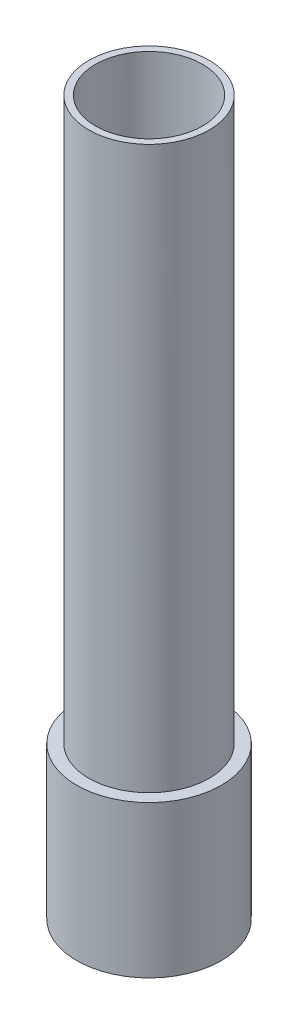
SolidWorks part; units mm, degrees
material "AISI 1020"
ref_plane "Front Plane" through (0, 0, 0) normal (0, 0, 1) x (1, 0, 0)
ref_plane "Top Plane" through (0, 0, 0) normal (0, 1, 0) x (1, 0, 0)
ref_plane "Right Plane" through (0, 0, 0) normal (1, 0, 0) x (0, 0, -1)
sketch "Sketch1" plane through (0, 0, 0) normal (0, 1, 0) x (1, 0, 0)
  circle A0 centre (13.6327, 6.0794) radius 7.0485
  circle A1 centre (13.6327, 6.0794) radius 7.9375
  dimension "D1" = 14.097
  dimension "D2" = 15.875
extrude "Boss-Extrude1" add sketch "Sketch1" along normal blind 93.93
sketch "Sketch2" plane through (0, 0, 0) normal (0, -1, 0) x (1, 0, 0)
  circle A0 centre (13.6327, -6.0794) radius 7.9375
  circle A1 centre (13.6327, -6.0794) radius 9.525
  dimension "D1" = 19.05
extrude "Boss-Extrude2" add sketch "Sketch2" against normal blind 20
sketch "Sketch3" plane through (0, 0, 0) normal (0, -1, 0) x (1, 0, 0)
  circle A0 centre (13.6327, -6.0794) radius 8.335
  dimension "D1" = 16.67
extrude "Cut-Extrude1" cut sketch "Sketch3" against normal blind 16.0867
